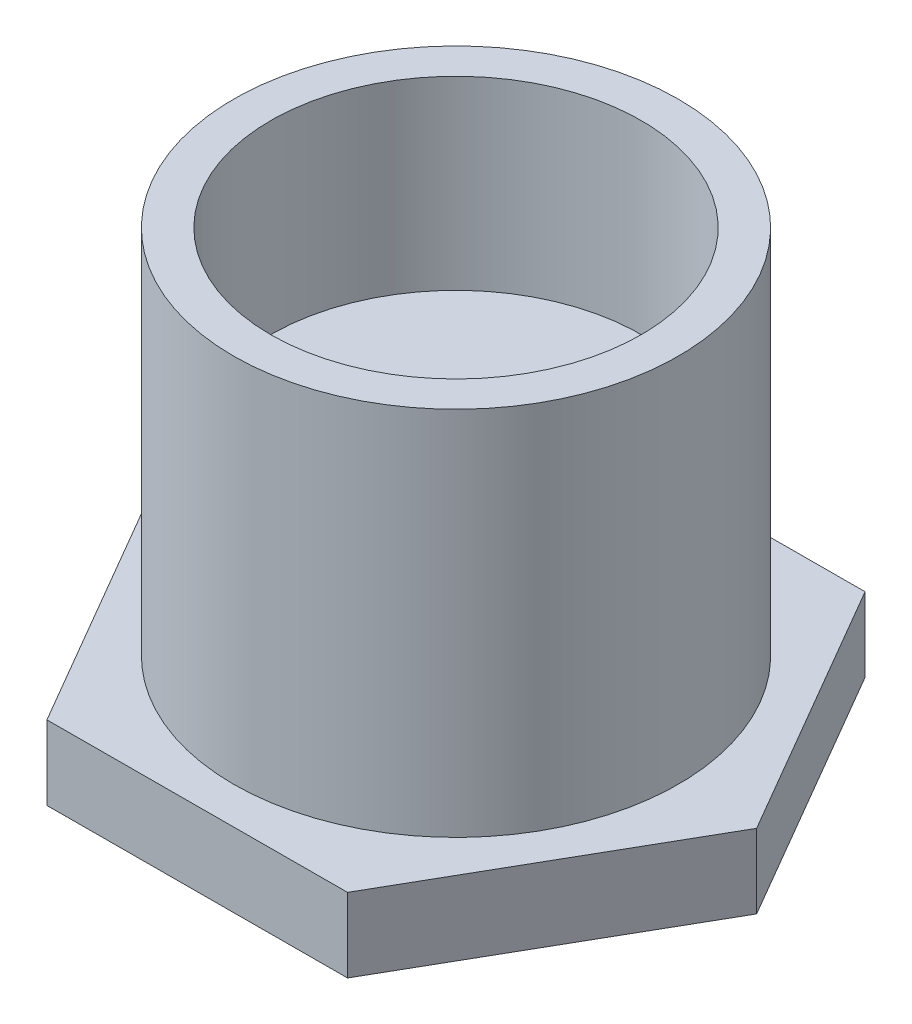
SolidWorks part; units mm, degrees
material "1.4000 (X6Cr13)"
ref_plane "正面" through (0, 0, 0) normal (0, 0, 1) x (1, 0, 0)
ref_plane "平面" through (0, 0, 0) normal (0, 1, 0) x (1, 0, 0)
ref_plane "右側面" through (0, 0, 0) normal (1, 0, 0) x (0, 0, -1)
sketch "ｽｹｯﾁ1" plane through (0, 0, 0) normal (0, 1, 0) x (1, 0, 0)
  line L1 (4.0629, -6.9876) -> (8.0829, 0.0248)
  line L2 (8.0829, 0.0248) -> (4.0199, 7.0124)
  line L3 (4.0199, 7.0124) -> (-4.0629, 6.9876)
  line L4 (-4.0629, 6.9876) -> (-8.0829, -0.0248)
  line L5 (-8.0829, -0.0248) -> (-4.0199, -7.0124)
  line L6 (-4.0199, -7.0124) -> (4.0629, -6.9876)
  circle A0 centre (0, 0) radius 7 construction
  dimension "D1" = 14
extrude "ﾎﾞｽ - 押し出し1" add sketch "ｽｹｯﾁ1" along normal blind 2
sketch "ｽｹｯﾁ2" plane through (0, 2, 0) normal (0, 1, 0) x (1, 0, 0)
  circle A0 centre (0, 0) radius 6
extrude "ﾎﾞｽ - 押し出し2" add sketch "ｽｹｯﾁ2" along normal blind 10
sketch "ｽｹｯﾁ3" plane through (0, 12, 0) normal (0, 1, 0) x (1, 0, 0)
  circle A0 centre (0, 0) radius 5
extrude "ｶｯﾄ - 押し出し1" cut sketch "ｽｹｯﾁ3" against normal blind 5
